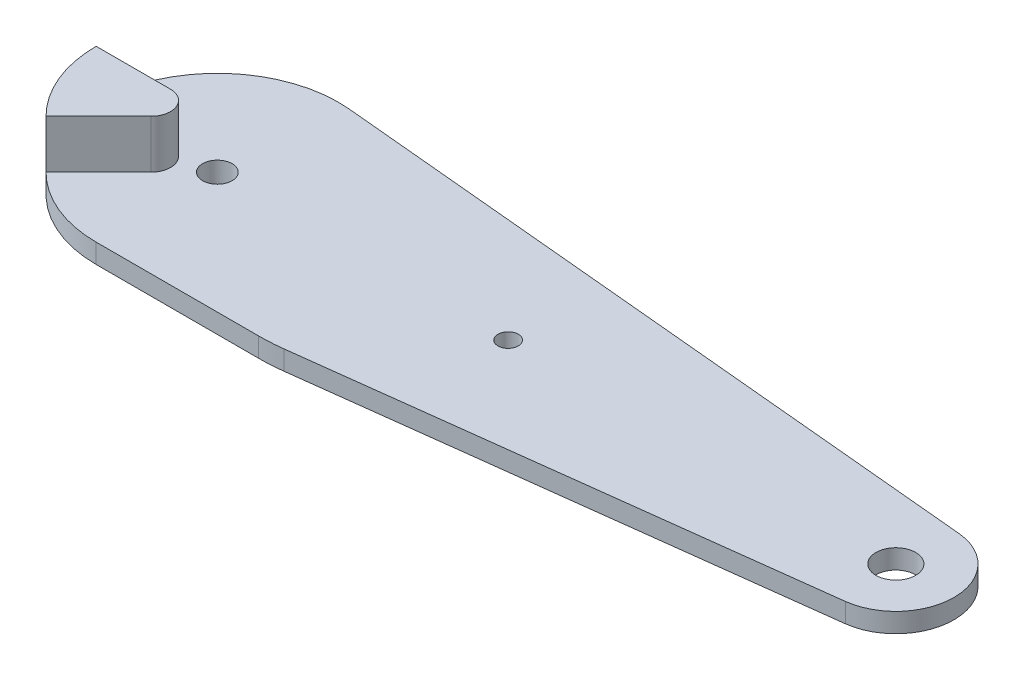
SolidWorks part; units mm, degrees
material "ABS"
ref_plane "前视基准面" through (0, 0, 0) normal (0, 0, 1) x (1, 0, 0)
ref_plane "上视基准面" through (0, 0, 0) normal (0, 1, 0) x (1, 0, 0)
ref_plane "右视基准面" through (0, 0, 0) normal (1, 0, 0) x (0, 0, -1)
other "Configuration Table"
sketch "草图1" plane through (0, 0, 0) normal (0, 1, 0) x (1, 0, 0)
  circle A0 centre (0, 0) radius 3.05
  circle A1 centre (0, 0) radius 12.5
  dimension "D1" = 6.1
  dimension "D2" = 25
extrude "凸台-拉伸1" add sketch "草图1" along normal blind 8 contours A0 | A1
sketch "草图2" plane through (0, 0, 0) normal (0, 0, 1) x (1, 0, 0)
  line L0 (12.5, 0) -> (12.5, 8) construction
  line L1 (-12.5, 8) -> (-12.5, 0) construction
  line L2 (-12.5, 0) -> (12.5, 0) construction
  line L3 (12.5, 8) -> (-12.5, 8) construction
  line L4 (12.5, 0) -> (12.5, 8) construction
  line L5 (-12.5, 8) -> (-12.5, 0) construction
  line L6 (-12.5, 0) -> (12.5, 0) construction
  line L7 (12.5, 8) -> (-12.5, 8) construction
  line L8 (-6.308, 1.7) -> (8.467, 1.7) construction
  circle A0 centre (0, 3.3) radius 1.6
  dimension "D1" = 3.2
  dimension "D2" = 3.3
extrude "切除-拉伸4" cut sketch "草图2" against normal mid plane 25
sketch "草图3" plane through (0, 8, 0) normal (0, 1, 0) x (1, 0, 0)
  line L0 (2.3214, 24.892) -> (141.1143, 11.9482)
  line L2 (0, -25) -> (36, -25)
  line L3 (36, -25) -> (141.478, -11.9086)
  line L4 (0, 0) -> (60, 0) construction
  circle A0 centre (0, 0) radius 12.5 construction
  circle A1 centre (0, 0) radius 12.5 construction
  circle A2 centre (140, 0) radius 4.1
  circle A3 centre (60, 0) radius 2.1
  arc A5 (141.478, -11.9086) -> (141.1143, 11.9482) centre (140, 0) ccw
  arc A6 (0, -25) -> (2.3214, 24.892) centre (0, 0) cw
  dimension "D1" = 8.2
  dimension "D3" = 60
  dimension "D4" = 25
  dimension "D5" = 4.2
  dimension "D6" = 12
  dimension "D7" = 36
  dimension "D2" = 140
extrude "凸台-拉伸2" add sketch "草图3" along normal blind 4 contours L0 A5 L3 L2 A6 | A3 | A2
sketch "草图4" plane through (0, 8, 0) normal (0, -1, 0) x (1, 0, 0)
  line L2 (2.3214, -24.892) -> (141.1143, -11.9482)
  line L3 (141.478, 11.9086) -> (36, 25)
  line L4 (2.3214, -24.892) -> (141.1143, -11.9482) construction
  line L7 (141.478, 11.9086) -> (36, 25) construction
  line L8 (36, 25) -> (0, 25)
  line L9 (36, 25) -> (0, 25) construction
  circle A0 centre (0, 0) radius 12.5 construction
  circle A1 centre (0, 0) radius 12.5 construction
  circle A2 centre (0, 0) radius 18
  arc A4 (0, 25) -> (2.3214, -24.892) centre (0, 0) ccw
  arc A5 (141.1143, -11.9482) -> (141.478, 11.9086) centre (140, 0) ccw
  arc A6 (0, 25) -> (2.3214, -24.892) centre (0, 0) ccw construction
  arc A7 (141.1143, -11.9482) -> (141.478, 11.9086) centre (140, 0) ccw construction
  dimension "D2" = 36
  dimension "D1" = 0
extrude "凸台-拉伸3" add sketch "草图4" along normal blind 2
fillet "圆角2" radius 40 1 edges at (36, 10, 25)
fillet "圆角1" radius 1 1 edges at (0, 6, -18)
sketch "草图5" plane through (0, 12, 0) normal (0, 1, 0) x (1, 0, 0)
  line L0 (0, 0) -> (-25, 0)
  line L1 (-41.2824, 0) -> (201.9647, 0) construction
  line L2 (0, 0) -> (-17.6777, -17.6777)
  line L5 (0, -25) -> (33.5272, -25)
  line L6 (38.454, -24.6954) -> (141.478, -11.9086)
  line L7 (141.1143, 11.9482) -> (2.3214, 24.892)
  line L8 (0, -25) -> (33.5272, -25) construction
  line L9 (38.454, -24.6954) -> (141.478, -11.9086) construction
  line L10 (141.1143, 11.9482) -> (2.3214, 24.892) construction
  arc A0 (2.3214, 24.892) -> (0, -25) centre (0, 0) ccw construction
  arc A1 (-25, 0) -> (-17.6777, -17.6777) centre (0, 0) ccw
  arc A4 (33.5272, -25) -> (38.454, -24.6954) centre (33.5272, 15) ccw
  arc A5 (141.478, -11.9086) -> (141.1143, 11.9482) centre (140, 0) ccw
  arc A6 (2.3214, 24.892) -> (0, -25) centre (0, 0) ccw
  arc A7 (33.5272, -25) -> (38.454, -24.6954) centre (33.5272, 15) ccw construction
  arc A8 (141.478, -11.9086) -> (141.1143, 11.9482) centre (140, 0) ccw construction
  arc A9 (2.3214, 24.892) -> (0, -25) centre (0, 0) ccw construction
  dimension "D2" = 135
  dimension "D3" = 45
  dimension "D1" = 0
extrude "凸台-拉伸4" add sketch "草图5" along normal blind 10
fillet "圆角3" radius 4 1 edges at (0, 17, 0)
sketch "草图6" plane through (0, 0, 0) normal (0, -1, 0) x (1, 0, 0)
  circle A0 centre (0, 0) radius 3.05 construction
  circle A1 centre (0, 0) radius 3.05
extrude "切除-拉伸5" cut sketch "草图6" against normal up to surface (12 mm away) up to face at (140, 12, 4.1)
sketch "草图7" plane through (0, 0, 0) normal (0, -1, 0) x (1, 0, 0)
  line L0 (0, 0) -> (0, 12.5) construction
  line L1 (-5.9372, 11) -> (5.9372, 11)
  line L2 (-5.9372, -11) -> (5.9372, -11)
  arc A0 (5.9372, 11) -> (-5.9372, 11) centre (0, 0) ccw
  circle A1 centre (0, 0) radius 12.5
  circle A2 centre (0, 0) radius 12.5 construction
  arc A3 (-5.9372, -11) -> (5.9372, -11) centre (0, 0) ccw
  circle M5 centre (0, 0) radius 12.5
  dimension "D2" = 11
  dimension "D3" = 11
  dimension "D1" = 0
extrude "切除-拉伸6" cut sketch "草图7" against normal up to surface (6 mm away) contours L1 M5 | L2 M5 up to face at (0, 6, -17)
